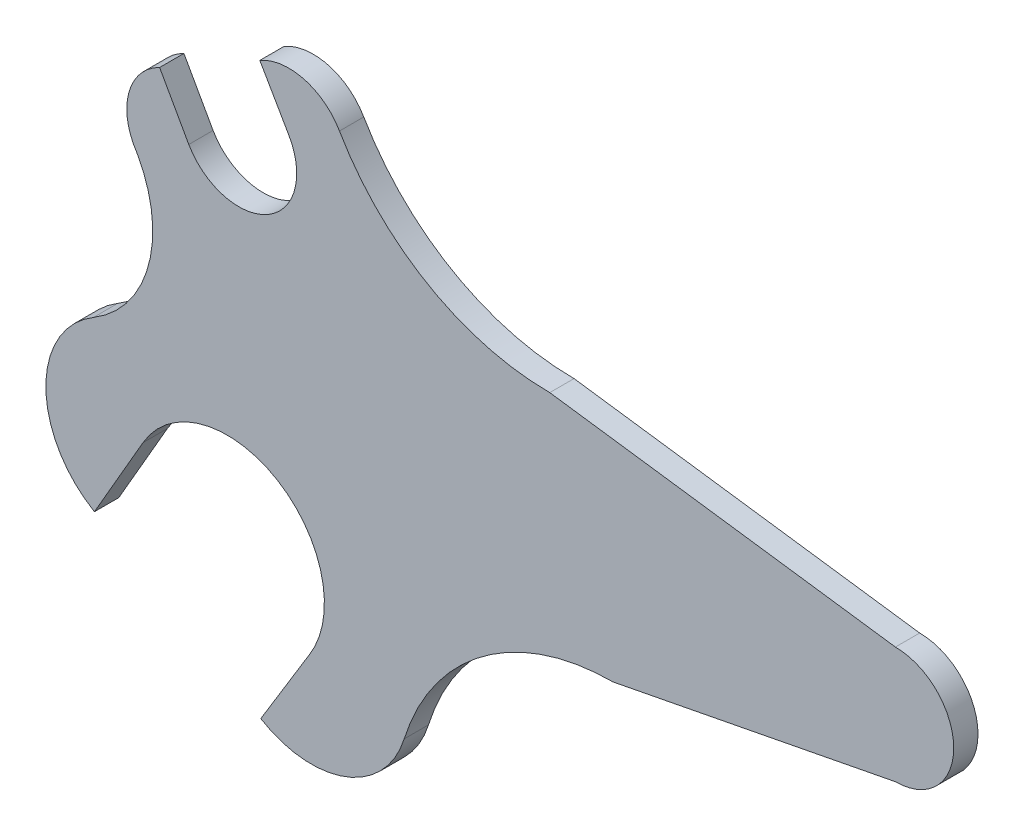
SolidWorks part; units mm, degrees
ref_plane "Front Plane" through (0, 0, 0) normal (0, 0, 1) x (1, 0, 0)
ref_plane "Top Plane" through (0, 0, 0) normal (0, 1, 0) x (1, 0, 0)
ref_plane "Right Plane" through (0, 0, 0) normal (1, 0, 0) x (0, 0, -1)
sketch "Sketch1" plane through (0, 0, 0) normal (0, 0, 1) x (1, 0, 0)
  line L0 (0, 0) -> (115, 0) construction
  line L1 (12.141, -58.9711) -> (6.5689, -68.6224) construction
  line L2 (0, 0) -> (0, 33.1113) construction
  line L3 (0, 0) -> (0, -32.0146) construction
  line L4 (0, 0) -> (-14.1479, 24.505) construction
  line L5 (-30.4101, 28.8624) -> (-41.0764, 22.0366) construction
  line L6 (0, 0) -> (-12.5, -21.6506) construction
  line L7 (-36.4101, 39.5887) -> (-30.4101, 28.8624)
  line L9 (-9.7905, 40.7671) -> (0.5733, 46.7506) construction
  line L11 (0, 0) -> (20.7846, 12) construction
  line L12 (-9.7905, 40.7671) -> (10.3923, 6) construction
  line L13 (0, -32.0146) -> (0, -71.2193) construction
  line L14 (0, 0) -> (34.641, -20) construction
  line L15 (34.641, -20) -> (25.2415, -36.2805) construction
  line L18 (-49.8205, -46.2917) -> (-50.2133, -46.0649) construction
  line L19 (-15.5925, -66.0532) -> (1.315, -75.8147) construction
  line L20 (-39.8205, -28.9711) -> (-50.0169, -46.1783) construction
  line L21 (-5.1795, -48.9711) -> (-15.5925, -66.0532) construction
  line L22 (-39.8205, -28.9711) -> (-49.8205, -46.2917)
  line L23 (-5.1795, -48.9711) -> (-15.5895, -66.0483)
  line L28 (-9.7905, 40.7671) -> (-15.7905, 51.1594)
  line L32 (56.8889, -23.2717) -> (115, -12)
  line L34 (43.8746, 21.7835) -> (115, 12)
  arc A0 (115, -12) -> (115, 12) centre (115, 0) ccw
  arc A1 (-5.6758, -49.7853) -> (-39.8205, -28.9711) centre (-22.5, -38.9711) ccw
  arc A2 (-30.4101, 28.8624) -> (-9.7905, 40.7671) centre (-20.1003, 34.8147) ccw
  arc A5 (-15.5895, -66.0483) -> (13.9185, -54.9098) centre (-5.1795, -48.9711) ccw
  arc A6 (-50.0441, -11.7816) -> (-49.8205, -46.2917) centre (-39.8205, -28.9711) ccw
  arc A7 (-50.0441, -11.7816) -> (-41.0764, 22.0366) centre (-62.8235, 9.7052) ccw
  arc A8 (-36.4101, 39.5887) -> (-41.0764, 22.0366) centre (-31.162, 28.7972) ccw
  arc A10 (56.8889, -23.2717) -> (13.9185, -54.9098) centre (56.8889, -68.2717) ccw
  arc A11 (0.6018, 46.7671) -> (43.8746, 21.7835) centre (43.8746, 71.7506) ccw
  arc A12 (0.6018, 46.7671) -> (-15.7905, 51.1594) centre (-9.7905, 40.7671) ccw
  dimension "D3" = 30
  dimension "D4" = 30
extrude "Boss-Extrude2" add sketch "Sketch1" along normal blind 5 contours A11 A12 L28 A2 L7 A8 A7 A6 L22 A1 L23 A5 A10 L32 A0 L34
